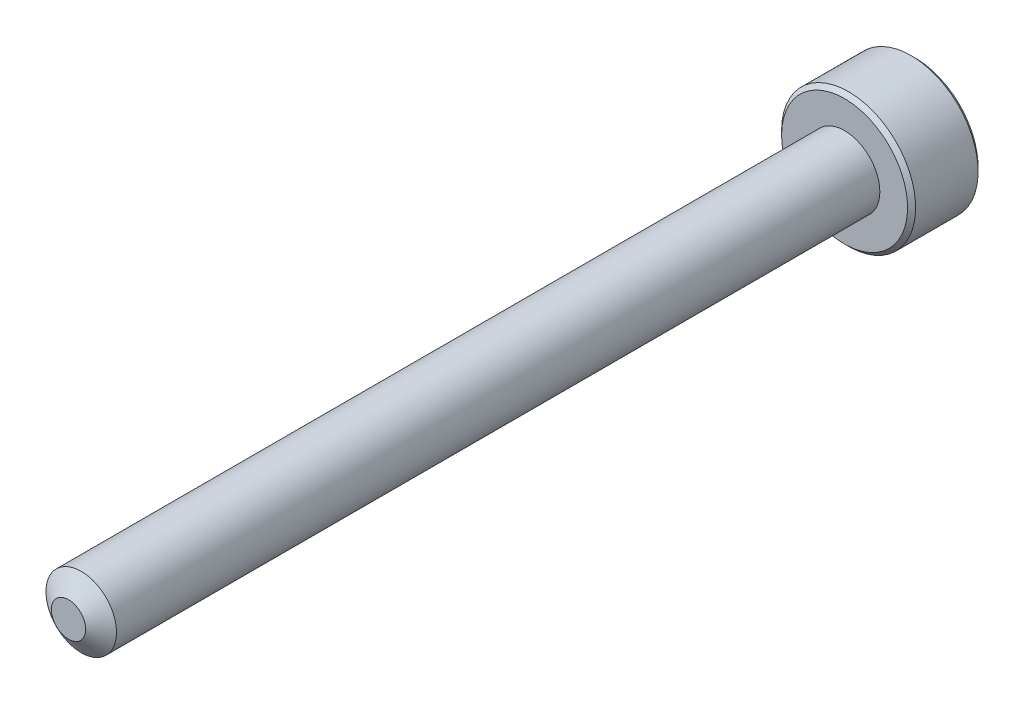
SolidWorks part; units mm, degrees
ref_plane "Front Plane" through (0, 0, 0) normal (0, 0, 1) x (1, 0, 0)
ref_plane "Top Plane" through (0, 0, 0) normal (0, 1, 0) x (1, 0, 0)
ref_plane "Right Plane" through (0, 0, 0) normal (1, 0, 0) x (0, 0, -1)
sketch "Sketch1" plane through (0, 0, 0) normal (0, 0, 1) x (1, 0, 0)
  circle A0 centre (0, 0) radius 1
  dimension "OD" = 2
extrude "Extrude1" add sketch "Sketch1" against normal blind 22
cosmetic thread "Cosmetic Thread1" parameters "D1"=21.6402, "D2"=1.548
sketch "Sketch2" plane through (0, 0, 0) normal (0, 0, 1) x (1, 0, 0)
  circle A0 centre (0, 0) radius 1 construction
  circle A1 centre (0, 0) radius 1
sketch "Sketch3" plane through (0, 0, 0) normal (1, 0, 0) x (0, 0, -1)
  line L0 (-0.35, 1) -> (-0.2, 0.7402)
  line L1 (-0.2, 0.7402) -> (-0.15, 0.7402)
  line L2 (-0.15, 0.7402) -> (0, 1)
  line L3 (-0.35, 1) -> (0, 1)
  line L4 (-0.175, 1) -> (-0.175, 0.7402) construction
  line L5 (-0.275, 0.8701) -> (-0.075, 0.8701) construction
  line L6 (0, 1) -> (0, -1) construction
  line L7 (0, -1) -> (22, -1) construction
  point P11 (1.8, -1)
  dimension "D1" = 0.05
  dimension "D2" = 0.2
  dimension "D3" = 60
  dimension "D4" = 1.8
sketch "Sketch4" plane through (0, 0, 0) normal (1, 0, 0) x (0, 0, -1)
  line L0 (0.3598, 1) -> (0, 0.4862)
  line L1 (0, 0.4862) -> (0, 1)
  line L2 (0.3598, 1) -> (0, 1)
  line L3 (-0.35, 1) -> (0, 1) construction
  line L4 (0, 0) -> (7.0209, 0) construction
  dimension "D1" = 55
  dimension "D2" = 0.254
revolve "Cut-Revolve1" cut sketch "Sketch4" angle 360 about L4
sketch "Sketch6" plane through (0, 0, -22) normal (0, 0, -1) x (-1, 0, 0)
  circle A0 centre (0, 0) radius 1.9
  dimension "head dia" = 3.8
extrude "Extrude2" add sketch "Sketch6" along normal blind 2
sketch "Sketch7" plane through (0, 0, -24) normal (0, 0, -1) x (-1, 0, 0)
  line L1 (0, 0.866) -> (-0.75, 0.433)
  line L2 (-0.75, 0.433) -> (-0.75, -0.433)
  line L3 (-0.75, -0.433) -> (0, -0.866)
  line L4 (0, -0.866) -> (0.75, -0.433)
  line L5 (0.75, -0.433) -> (0.75, 0.433)
  line L6 (0.75, 0.433) -> (0, 0.866)
  circle A0 centre (0, 0) radius 0.75 construction
  dimension "hex dia" = 1.5
extrude "Cut-Extrude1" cut sketch "Sketch7" against normal blind 1.125
sketch "Sketch8" plane through (0, 0, -24) normal (0, 0, -1) x (-1, 0, 0)
  circle A0 centre (0, 0) radius 0.866
extrude "Cut-Extrude2" cut sketch "Sketch8" against normal through all draft 45
chamfer "Chamfer1" distance 0.114 angle 45 2 edges at (-1.9, 0, -24) (-1.9, 0, -22)
sketch "Sketch9" plane through (0, 0, 0) normal (1, 0, 0) x (0, 0, -1)
  line L0 (0, 1) -> (0, -1) construction
  line L1 (2.2, 1) -> (2.2, -1) construction
  dimension "D1" = 2.2
sketch "Sketch10" plane through (0, 0, 0) normal (1, 0, 0) x (0, 0, -1)
  line L0 (22, 1) -> (22, 0)
  line L1 (22, 1) -> (21.9, 1)
  line L2 (21.9, 1) -> (21.4858, 0)
  line L3 (22, 0) -> (21.4858, 0)
  line L4 (22, 1.786) -> (22, -1.786) construction
  dimension "D1" = 22.5
  dimension "D2" = 0.1
revolve "Revolve1" add sketch "Sketch10" angle 360 about L3
